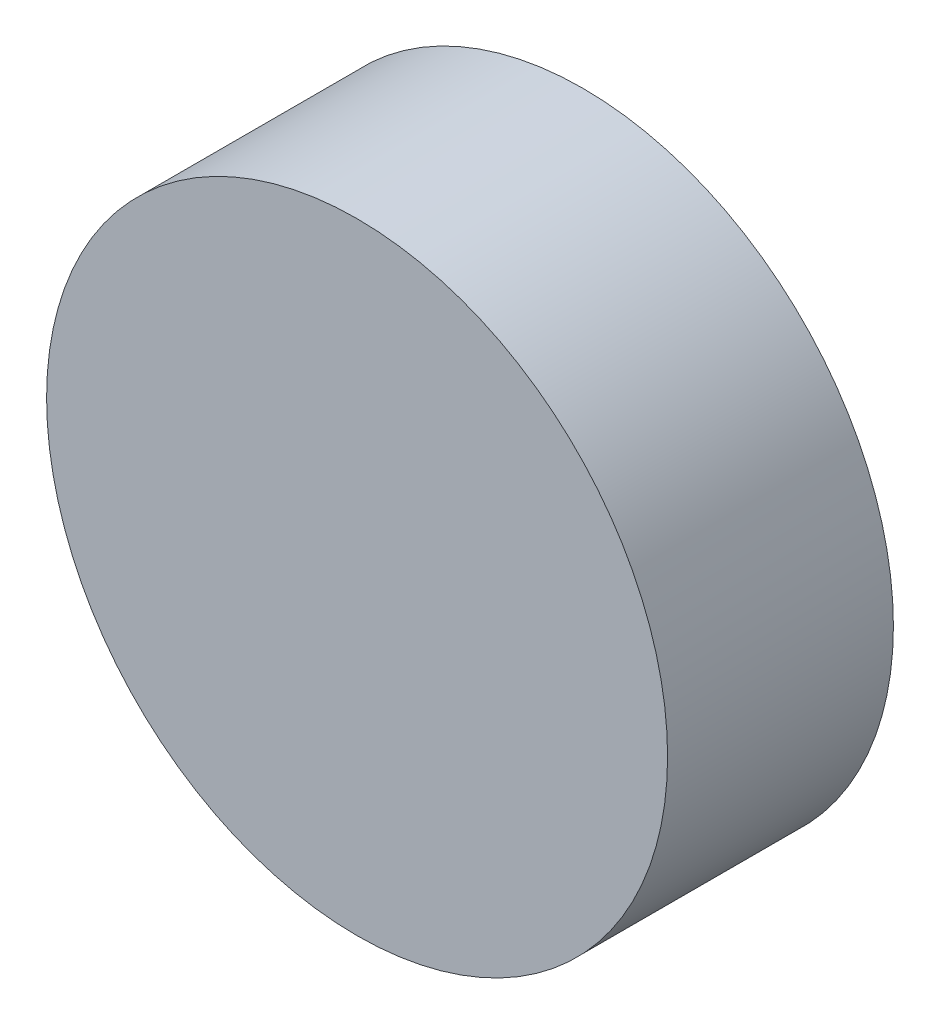
SolidWorks part; units mm, degrees
ref_plane "前基準面" through (0, 0, 0) normal (0, 0, 1) x (1, 0, 0)
ref_plane "上基準面" through (0, 0, 0) normal (0, 1, 0) x (1, 0, 0)
ref_plane "右基準面" through (0, 0, 0) normal (1, 0, 0) x (0, 0, -1)
sketch "草圖1" plane through (0, 0, 0) normal (0, 0, 1) x (1, 0, 0)
  circle A0 centre (0, 0) radius 55
  dimension "D1" = 110
extrude "填料-伸長1" add sketch "草圖1" along normal blind 40 contours A0
sketch "草圖2" plane through (0, 0, 0) normal (0, 0, -1) x (-1, 0, 0)
  point P0 (0, 0)
  point P1 (0, 0)
sketch "草圖3" plane through (0, 0, 0) normal (0, 0, -1) x (-1, 0, 0)
  circle A0 centre (0, 0) radius 25
extrude "除料-伸長1" cut sketch "草圖3" against normal blind 20
sketch "草圖4" plane through (0, 0, 40) normal (0, 0, 1) x (1, 0, 0)
  point P0 (0, 0)
